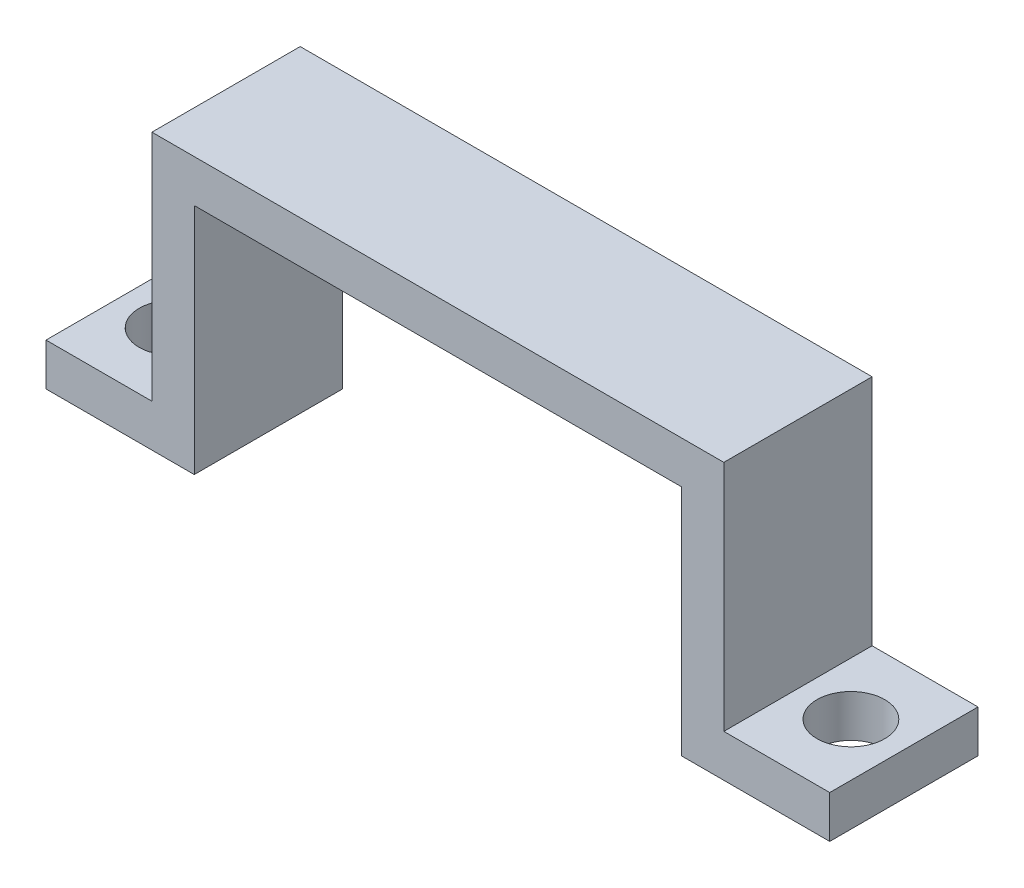
SolidWorks part; units mm, degrees
ref_plane "前基準面" through (0, 0, 0) normal (0, 0, 1) x (1, 0, 0)
ref_plane "上基準面" through (0, 0, 0) normal (0, 1, 0) x (1, 0, 0)
ref_plane "右基準面" through (0, 0, 0) normal (1, 0, 0) x (0, 0, -1)
sketch "草圖1" plane through (0, 0, 0) normal (0, 0, 1) x (1, 0, 0)
  line L0 (-13.5, 0) -> (13.5, 0)
  line L1 (13.5, 0) -> (13.5, -11)
  line L2 (-13.5, 0) -> (-13.5, -11)
  line L3 (13.5, -11) -> (18.5, -11)
  line L4 (-13.5, -11) -> (-18.5, -11)
  line L5 (-18.5, -11) -> (-18.5, -13)
  line L6 (-18.5, -13) -> (-11.5, -13)
  line L7 (-11.5, -13) -> (-11.5, -2)
  line L8 (-11.5, -2) -> (11.5, -2)
  line L9 (11.5, -2) -> (11.5, -13)
  line L10 (11.5, -13) -> (18.5, -13)
  line L11 (18.5, -13) -> (18.5, -11)
  point P4 (0, 0)
extrude "填料-伸長1" add sketch "草圖1" along normal blind 7
sketch "草圖2" plane through (0, -11, 0) normal (0, 1, 0) x (1, 0, 0)
  circle A0 centre (16, -3.5) radius 1.6
  circle A1 centre (-16, -3.5) radius 1.6
extrude "除料-伸長1" cut sketch "草圖2" against normal blind 2
